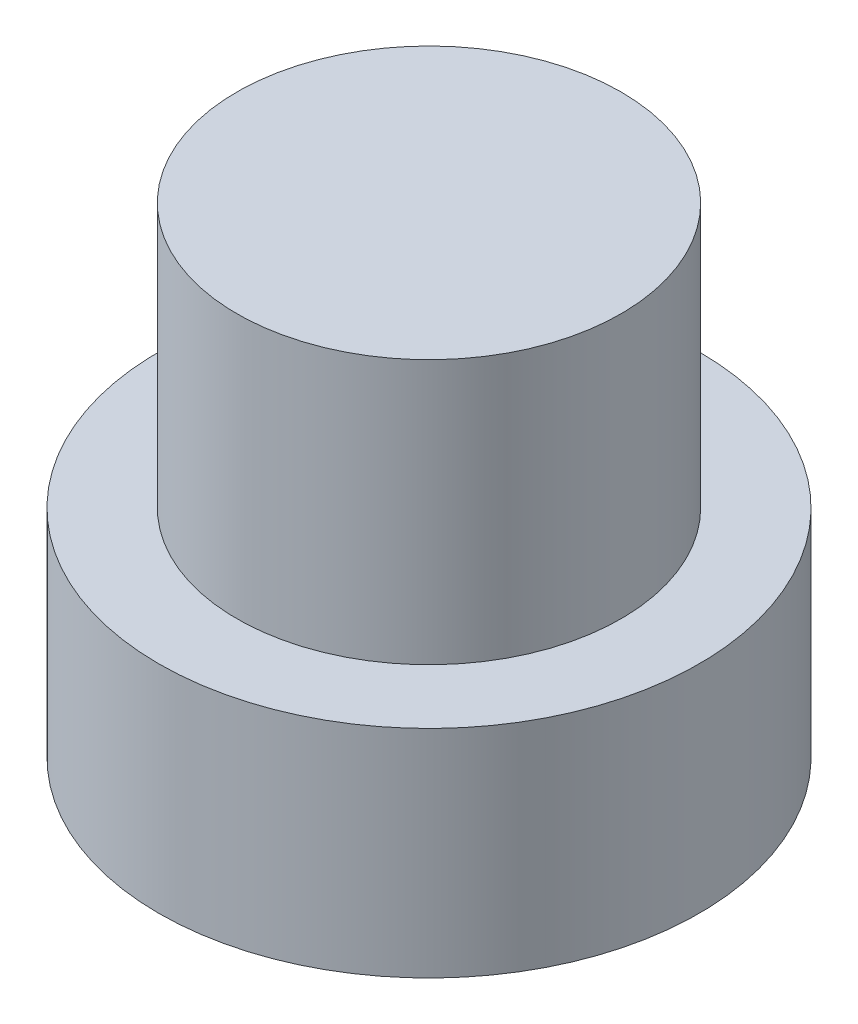
SolidWorks part; units mm, degrees
ref_plane "Front Plane" through (0, 0, 0) normal (0, 0, 1) x (1, 0, 0)
ref_plane "Top Plane" through (0, 0, 0) normal (0, 1, 0) x (1, 0, 0)
ref_plane "Right Plane" through (0, 0, 0) normal (1, 0, 0) x (0, 0, -1)
sketch "Sketch1" plane through (0, 0, 0) normal (0, 0, 1) x (1, 0, 0)
  line L0 (0, 0) -> (0, 68.6948) construction
  line L1 (0, 0) -> (22.5, 0)
  line L2 (22.5, 0) -> (22.5, 18)
  line L3 (22.5, 18) -> (16, 18)
  line L4 (16, 18) -> (16, 40)
  line L5 (16, 40) -> (0, 40)
  line L8 (1.5, 1.5) -> (21, 1.5)
  line L9 (21, 1.5) -> (21, 16.5)
  line L10 (21, 16.5) -> (14.5, 16.5)
  line L11 (14.5, 16.5) -> (14.5, 38.5)
  line L12 (14.5, 38.5) -> (1.5, 38.5)
  line L13 (1.5, 1.5) -> (0, 1.5)
  line L14 (1.5, 38.5) -> (0, 38.5)
  line L15 (0, 1.5) -> (0, 0)
  line L16 (1.5, 38.5) -> (1.5, 1.5) construction
  line L17 (0, 40) -> (0, 0) construction
  line L18 (0, 40) -> (0, 38.5)
  dimension "D1" = 22.5
  dimension "D2" = 1.5
revolve "Revolve1" add sketch "Sketch1" angle 360 about L0
equation "\"Housing_OD\"= 45mm"
equation "\"Housing_Wall\"= 1.5mm"
equation "\"Stack_ID\"= 28mm"
equation "\"Ampoule_OD\"= 25.5mm"
equation "\"Cell_Height\"= 1.66mm"
equation "\"D1@Sketch1\"=\"Housing_OD\"/2"
equation "\"D2@Sketch1\"=\"Housing_Wall\""
